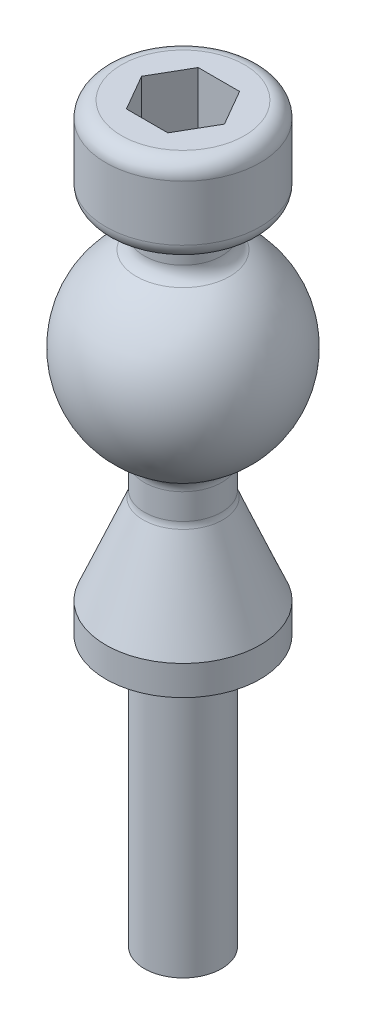
SolidWorks part; units mm, degrees
material "1023 Carbon Steel Sheet (SS)"
ref_plane "Front Plane" through (0, 0, 0) normal (0, 0, 1) x (1, 0, 0)
ref_plane "Top Plane" through (0, 0, 0) normal (0, 1, 0) x (1, 0, 0)
ref_plane "Right Plane" through (0, 0, 0) normal (1, 0, 0) x (0, 0, -1)
sketch "Sketch1" plane through (0, 0, 0) normal (0, 0, 1) x (1, 0, 0)
  line L0 (0, 15.24) -> (0, -8.89)
  line L1 (0, 15.24) -> (2.0245, 15.24)
  line L2 (2.54, 14.7245) -> (2.54, 12.898)
  line L3 (2.0245, 12.3825) -> (1.7855, 12.3825)
  line L4 (1.27, 11.867) -> (1.27, 11.4324)
  line L5 (1.27, 4.9727) -> (1.27, 4.1257)
  line L6 (1.3097, 3.9275) -> (2.54, 0.9746)
  line L7 (2.54, 0.9746) -> (2.54, 0)
  line L8 (2.54, 0) -> (1.27, 0)
  line L9 (1.27, 0) -> (1.27, -8.89)
  line L10 (0, -8.89) -> (1.27, -8.89)
  arc A0 (1.5361, 10.9812) -> (1.5361, 5.4239) centre (0, 8.2026) cw
  arc A1 (1.27, 4.1257) -> (1.3097, 3.9275) centre (1.7855, 4.1257) ccw
  arc A2 (1.5361, 5.4239) -> (1.27, 4.9727) centre (1.7855, 4.9727) ccw
  arc A3 (1.27, 11.4324) -> (1.5361, 10.9812) centre (1.7855, 11.4324) ccw
  arc A4 (1.7855, 12.3825) -> (1.27, 11.867) centre (1.7855, 11.867) ccw
  arc A5 (2.54, 12.898) -> (2.0245, 12.3825) centre (2.0245, 12.898) cw
  arc A6 (2.0245, 15.24) -> (2.54, 14.7245) centre (2.0245, 14.7245) cw
  point P9 (1.27, 4.0226)
  point P17 (1.27, 5.2926)
  point P22 (1.27, 11.1125)
  point P25 (1.27, 12.3825)
  point P28 (2.54, 12.3825)
  point P31 (2.54, 15.24)
  dimension "D6" = 3.175
  dimension "D11" = 0.5155
  dimension "D12" = 0.5155
  dimension "D1" = 24.13
  dimension "D2" = 2.54
  dimension "D3" = 1.27
  dimension "D4" = 15.24
  dimension "D5" = 2.8575
  dimension "D7" = 1.27
  dimension "D8" = 1.27
  dimension "D9" = 3.048
  dimension "D10" = 2.54
revolve "Revolve1" add sketch "Sketch1" angle 360 about L0
sketch "Sketch2" plane through (0, 15.24, 0) normal (0, 1, 0) x (1, 0, 0)
  line L0 (-1.3638, 0) -> (1.3638, 0) construction
  line L1 (-1.3638, 0) -> (-0.6819, -1.1811)
  line L2 (-0.6819, -1.1811) -> (0.6819, -1.1811)
  line L3 (0.6819, -1.1811) -> (1.3638, 0)
  line L4 (1.3638, 0) -> (0.6819, 1.1811)
  line L5 (0.6819, 1.1811) -> (-0.6819, 1.1811)
  line L6 (-0.6819, 1.1811) -> (-1.3638, 0)
  circle A0 centre (0, 0) radius 1.1811 construction
  dimension "D1" = 2.3622
extrude "Cut-Extrude2" cut sketch "Sketch2" against normal blind 2.54
